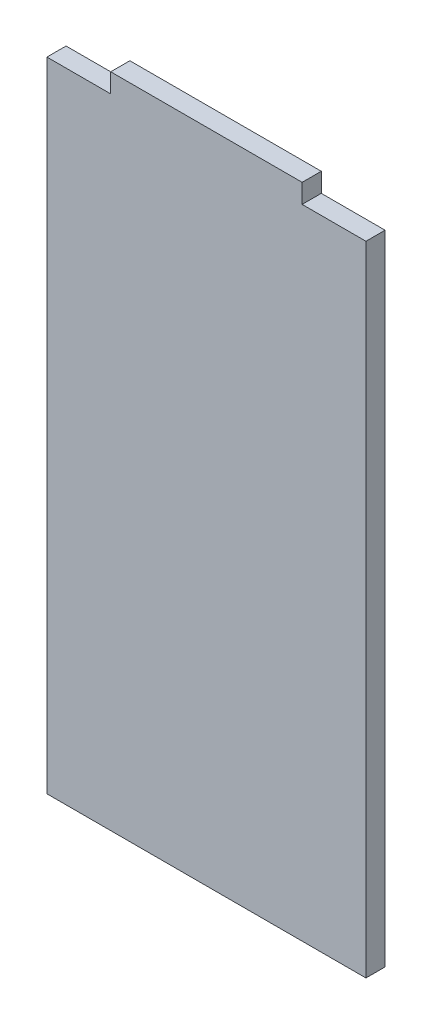
SolidWorks part; units mm, degrees
material "ABS"
ref_plane "Спереди" through (0, 0, 0) normal (0, 0, 1) x (1, 0, 0)
ref_plane "Сверху" through (0, 0, 0) normal (0, 1, 0) x (1, 0, 0)
ref_plane "Справа" through (0, 0, 0) normal (1, 0, 0) x (0, 0, -1)
sketch "Эскиз1" plane through (0, 0, 0) normal (0, 0, 1) x (1, 0, 0)
  line L1 (-25, -50) -> (25, -50)
  line L2 (-25, -50) -> (-25, 50)
  line L3 (-25, 50) -> (25, 50)
  line L4 (25, -50) -> (25, 50)
  line L5 (-25, -50) -> (25, 50) construction
  line L6 (-25, 50) -> (25, -50) construction
  line L7 (-15, 47) -> (15, 47)
  line L8 (-15, 47) -> (-15, 53)
  line L9 (-15, 53) -> (15, 53)
  line L10 (15, 47) -> (15, 53)
  line L11 (-15, 47) -> (15, 53) construction
  line L12 (-15, 53) -> (15, 47) construction
  point P0 (0, 0)
  point P6 (0, 50)
  dimension "D1" = 3
  dimension "D2" = 30
  dimension "D3" = 10
  dimension "D4" = 100
extrude "Бобышка-Вытянуть1" add sketch "Эскиз1" along normal blind 3 contours L10 L7 L8 L3 L2 L1 L4 | L7 L10 L3 L8 | L3 L10 L9 L8
